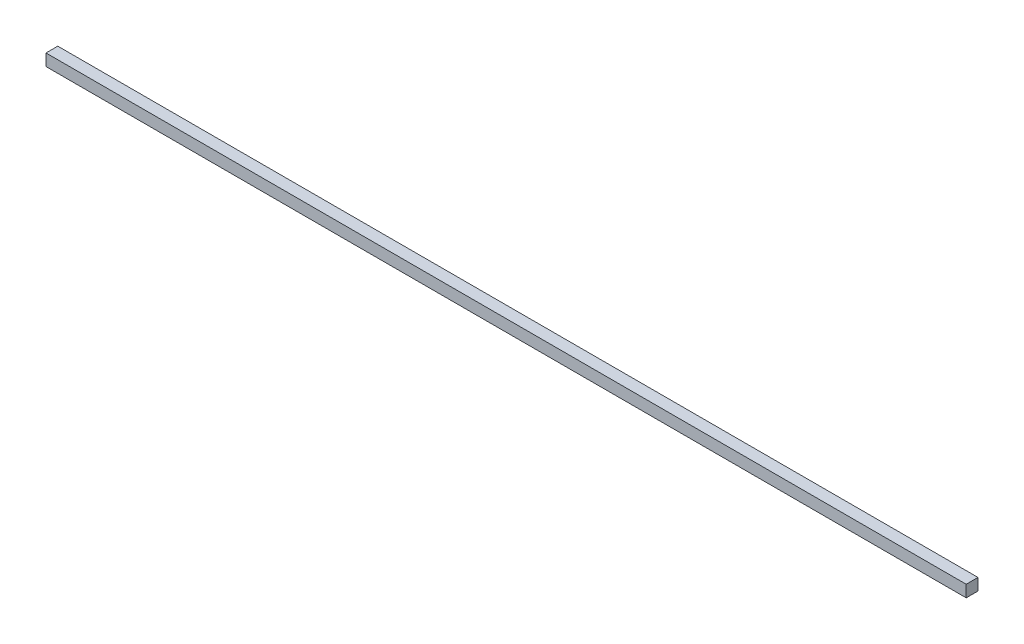
SolidWorks part; units mm, degrees
ref_plane "正面" through (0, 0, 0) normal (0, 0, 1) x (1, 0, 0)
ref_plane "平面" through (0, 0, 0) normal (0, 1, 0) x (1, 0, 0)
ref_plane "右側面" through (0, 0, 0) normal (1, 0, 0) x (0, 0, -1)
sketch "ｽｹｯﾁ1" plane through (0, 0, 0) normal (0, 0, 1) x (1, 0, 0)
  line L1 (-82.1516, 9.9786) -> (307.8484, 9.9786)
  line L2 (-82.1516, 9.9786) -> (-82.1516, 4.9786)
  line L3 (-82.1516, 4.9786) -> (307.8484, 4.9786)
  line L4 (307.8484, 9.9786) -> (307.8484, 4.9786)
  dimension "D3" = 5
  dimension "D4" = 390
extrude "ﾎﾞｽ - 押し出し1" add sketch "ｽｹｯﾁ1" along normal blind 5
